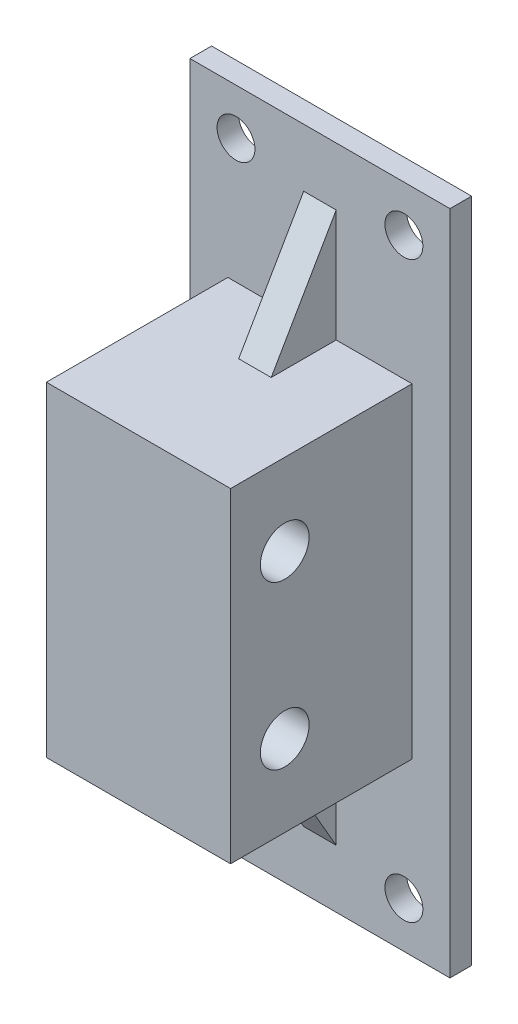
SolidWorks part; units mm, degrees
ref_plane "前视基准面" through (0, 0, 0) normal (0, 0, 1) x (1, 0, 0)
ref_plane "上视基准面" through (0, 0, 0) normal (0, 1, 0) x (1, 0, 0)
ref_plane "右视基准面" through (0, 0, 0) normal (1, 0, 0) x (0, 0, -1)
sketch "草图1" plane through (0, 0, 0) normal (0, 0, 1) x (1, 0, 0)
  line B0 (0, 0) -> (24, 0)
  line B1 (0, 61.5) -> (24, 61.5)
  line B2 (24, 61.5) -> (24, 0)
  line B3 (0, 0) -> (0, 61.5)
  line B4 (0, 45.75) -> (24, 45.75)
  line B5 (0, 15.75) -> (24, 15.75)
  line B6 (0, 38.25) -> (24, 38.25)
  line B7 (0, 23.25) -> (24, 23.25)
  line B8 (0, 40.32) -> (24, 40.32)
  line B9 (0, 36.18) -> (24, 36.18)
  line B10 (0, 25.32) -> (24, 25.32)
  line B11 (0, 21.18) -> (24, 21.18)
  circle B12 centre (5, 5) radius 1.75
  circle B13 centre (5, 56.5) radius 1.75
  circle B14 centre (19, 56.5) radius 1.75
  circle B15 centre (19, 5) radius 1.75
sketch_block_instance "块1-1"
sketch_block "块1"
sketch "草图2" plane through (0, 0, 0) normal (0, 0, 1) x (1, 0, 0)
  line L1 (0, 61.5) -> (24, 61.5)
  line L2 (0, 61.5) -> (0, 0)
  line L3 (0, 0) -> (24, 0)
  line L4 (24, 61.5) -> (24, 0)
  circle A0 centre (5, 56.5) radius 1.75 construction
  circle A1 centre (19, 56.5) radius 1.75 construction
  circle A2 centre (5, 5) radius 1.75 construction
  circle A3 centre (19, 5) radius 1.75 construction
  circle A4 centre (5, 56.5) radius 1.75
  circle A5 centre (19, 56.5) radius 1.75
  circle A6 centre (5, 5) radius 1.75
  circle A7 centre (19, 5) radius 1.75
extrude "凸台-拉伸1" add sketch "草图2" along normal blind 2
sketch "草图3" plane through (0, 0, 2) normal (0, 0, 1) x (1, 0, 0)
  line L0 (0, 61.5) -> (0, 0) construction
  line L1 (3.5, 45.75) -> (20.5, 45.75)
  line L2 (3.5, 45.75) -> (3.5, 15.75)
  line L3 (3.5, 15.75) -> (20.5, 15.75)
  line L4 (20.5, 45.75) -> (20.5, 15.75)
  line L5 (24, 0) -> (24, 61.5) construction
  line L6 (0, 15.75) -> (24, 15.75) construction
  line L7 (0, 45.75) -> (24, 45.75) construction
  dimension "D1" = 3.5
  dimension "D2" = 3.5
extrude "凸台-拉伸2" add sketch "草图3" along normal blind 16.75
sketch "草图4" plane through (24, 0, 0) normal (1, 0, 0) x (0, 0, -1)
  line L0 (-18.75, 45.75) -> (-2, 45.75) construction
  line L1 (-18.75, 15.75) -> (-2, 15.75) construction
  line L2 (-18.75, 15.75) -> (-18.75, 45.75) construction
  circle A0 centre (-13.75, 23.25) radius 2.25
  circle A1 centre (-13.75, 38.25) radius 2.25
  dimension "D4" = 4.5
  dimension "D1" = 7.5
  dimension "D2" = 7.5
  dimension "D3" = 5
extrude "切除-拉伸1" cut sketch "草图4" against normal through all
ref_plane "基准面2" through (12, 0, 0) normal (1, 0, 0) x (0, 0, -1)
sketch "草图5" plane through (12, 0, 0) normal (1, 0, 0) x (0, 0, -1)
  line L0 (-2, 56.1423) -> (-2, 45.75)
  line L1 (-2, 0) -> (-2, 61.5) construction
  line L2 (-2, 45.75) -> (-8, 45.75)
  line L3 (-18.75, 45.75) -> (-2, 45.75) construction
  line L4 (-8, 45.75) -> (-2, 56.1423)
  line L5 (-2, 15.75) -> (-2, 5.3577)
  line L6 (-2, 5.3577) -> (-8, 15.75)
  line L8 (-8, 15.75) -> (-2, 15.75)
  dimension "D1" = 60
  dimension "D2" = 60
  dimension "D3" = 6
  dimension "D4" = 6
extrude "凸台-拉伸3" add sketch "草图5" along normal mid plane 3
sketch "草图6" plane through (0, 0, 2) normal (0, 0, 1) x (1, 0, 0)
  circle A0 centre (5, 56.5) radius 1.75 construction
  circle A1 centre (19, 56.5) radius 1.75 construction
  circle A2 centre (19, 5) radius 1.75 construction
  circle A3 centre (5, 5) radius 1.75 construction
  circle A4 centre (5, 56.5) radius 1.75
  circle A5 centre (19, 56.5) radius 1.75
  circle A6 centre (19, 5) radius 1.75
  circle A7 centre (5, 5) radius 1.75
extrude "凸台-拉伸4" add sketch "草图6" against normal up to vertex (2 mm away)
sketch "草图7" plane through (0, 0, 2) normal (0, 0, 1) x (1, 0, 0)
  line L0 (0, 0) -> (24, 0) construction
  line L1 (24, 0) -> (24, 61.5) construction
  line L2 (24, 61.5) -> (0, 61.5) construction
  line L3 (0, 61.5) -> (0, 0) construction
  circle A0 centre (4.25, 57.25) radius 1.75
  circle A1 centre (19.75, 57.25) radius 1.75
  circle A2 centre (4.25, 4.25) radius 1.75
  circle A3 centre (19.75, 4.25) radius 1.75
  dimension "D5" = 3.5
  dimension "D1" = 4.25
  dimension "D2" = 4.25
  dimension "D3" = 4.25
  dimension "D4" = 4.25
extrude "切除-拉伸2" cut sketch "草图7" against normal through all
